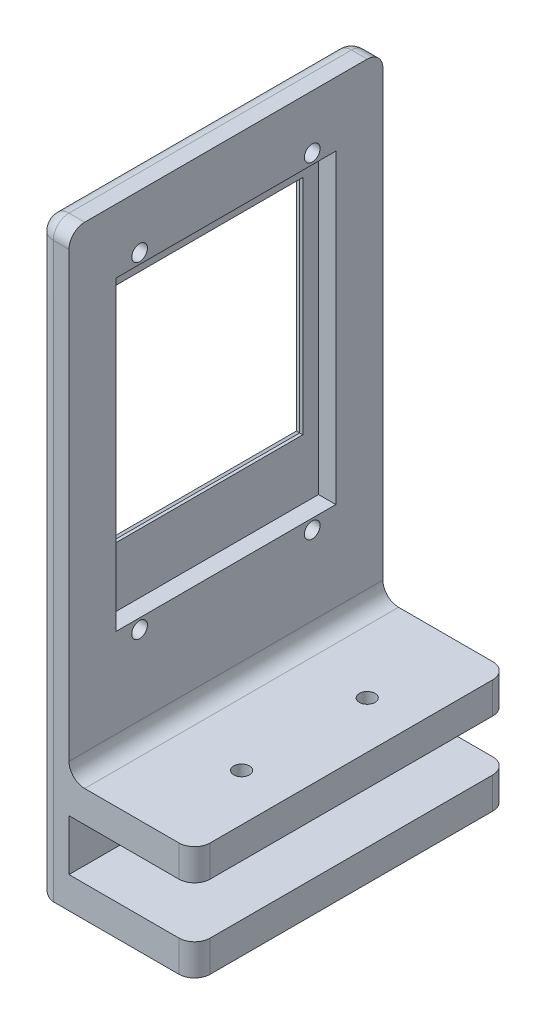
SolidWorks part; units mm, degrees
ref_plane "Front Plane" through (0, 0, 0) normal (0, 0, 1) x (1, 0, 0)
ref_plane "Top Plane" through (0, 0, 0) normal (0, 1, 0) x (1, 0, 0)
ref_plane "Right Plane" through (0, 0, 0) normal (1, 0, 0) x (0, 0, -1)
sketch "Sketch12" plane through (0, 0, 0) normal (0, 0, 1) x (1, 0, 0)
  line L0 (0, -38.4175) -> (20.32, -38.4175)
  line L1 (-5.08, 38.4175) -> (0, 38.4175)
  line L2 (-5.08, 38.4175) -> (-5.08, -56.8325)
  line L4 (0, 38.4175) -> (0, -38.4175)
  line L5 (20.32, -38.4175) -> (20.32, -43.4975)
  line L6 (20.32, -43.4975) -> (0, -43.4975)
  line L7 (0, -43.4975) -> (0, -51.7525)
  line L8 (20.32, -56.8325) -> (20.32, -51.7525)
  line L9 (20.32, -51.7525) -> (0, -51.7525)
  line L11 (20.32, -56.8325) -> (-5.08, -56.8325)
  dimension "D1" = 8.255
  dimension "D2" = 5.08
  dimension "D3" = 5.08
  dimension "D4" = 25.4
  dimension "D5" = 95.25
extrude "Boss-Extrude7" add sketch "Sketch12" along normal mid plane 50.8
sketch "Sketch14" plane through (0, 0, 0) normal (1, 0, 0) x (0, 0, -1)
  line L0 (-25.4, -43.4975) -> (25.4, -43.4975) construction
  line L1 (-15.24, 24.2443) -> (15.24, 24.2443)
  line L2 (-15.24, 24.2443) -> (-15.24, -11.8237)
  line L3 (-15.24, -11.8237) -> (15.24, -11.8237)
  line L4 (15.24, 24.2443) -> (15.24, -11.8237)
  line L5 (-15.24, 24.2443) -> (15.24, -11.8237) construction
  line L6 (-15.24, -11.8237) -> (15.24, 24.2443) construction
  point P0 (0, 6.2103)
  dimension "D1" = 36.068
  dimension "D2" = 30.48
  dimension "D3" = 49.7078
extrude "Cut-Extrude3" cut sketch "Sketch14" against normal through all
sketch "Sketch15" plane through (0, 0, 0) normal (1, 0, 0) x (0, 0, -1)
  line L0 (15.24, 24.2443) -> (-15.24, 24.2443) construction
  line L1 (-17.78, 28.0543) -> (17.78, 28.0543)
  line L2 (-17.78, 28.0543) -> (-17.78, -21.4757)
  line L3 (-17.78, -21.4757) -> (17.78, -21.4757)
  line L4 (17.78, 28.0543) -> (17.78, -21.4757)
  line L5 (-17.78, 28.0543) -> (17.78, -21.4757) construction
  line L6 (-17.78, -21.4757) -> (17.78, 28.0543) construction
  point P0 (0, 3.2893)
  dimension "D1" = 35.56
  dimension "D2" = 49.53
  dimension "D3" = 3.81
extrude "Cut-Extrude4" cut sketch "Sketch15" against normal blind 2.794
chamfer "Chamfer1" distance 1.778 angle 35 4 edges at (-5.08, -11.8237, 0) (-5.08, 6.2103, 15.24) (-5.08, 24.2443, 0) (-5.08, 6.2103, -15.24)
sketch "Sketch16" plane through (0, 0, 0) normal (1, 0, 0) x (0, 0, -1)
  line L0 (-25.4, 6.2103) -> (25.4, 6.2103) construction
  line L1 (25.4, -38.4175) -> (25.4, 38.4175) construction
  line L2 (-25.4, -38.4175) -> (-25.4, 38.4175) construction
  line L3 (-15.24, 24.2443) -> (15.24, 24.2443) construction
  circle A0 centre (-13.97, 29.7053) radius 1.27
  circle A1 centre (13.97, 29.7053) radius 1.27
  circle A2 centre (-13.97, -23.1267) radius 1.27
  circle A3 centre (13.97, -23.1267) radius 1.27
  dimension "D1" = 2.54
  dimension "D2" = 27.94
  dimension "D3" = 52.832
  dimension "D4" = 13.97
  dimension "D5" = 18.034
  dimension "D6" = 23.495
extrude "Cut-Extrude5" cut sketch "Sketch16" against normal through all
sketch "Sketch21" [suppressed] plane through (-2.794, 0, 0) normal (1, 0, 0) x (0, 0, -1)
  line L0 (15.24, 24.2443) -> (15.24, -11.8237) construction
  line L1 (15.24, 6.2103) -> (-15.24, 6.2103) construction
  line L2 (-15.24, -11.8237) -> (-15.24, 24.2443) construction
  point P0 (15.24, 6.2103)
fillet "Fillet4" radius 2.54 2 edges at (-2.54, 38.4175, -25.4) (-2.54, 38.4175, 25.4)
fillet "Fillet5" radius 2.54 4 edges at (20.32, -54.2925, 25.4) (20.32, -40.9575, 25.4) (20.32, -54.2925, -25.4) (20.32, -40.9575, -25.4)
sketch "Sketch23" plane through (0, -51.7525, 0) normal (0, 1, 0) x (1, 0, 0)
  line L0 (8.89, 25.4) -> (8.89, -25.4) construction
  line L1 (17.78, 25.4) -> (0, 25.4) construction
  line L2 (17.78, -25.4) -> (0, -25.4) construction
  line L3 (0, -25.4) -> (0, 25.4) construction
  circle A0 centre (8.89, 15.24) radius 1.778
  circle A1 centre (8.89, -15.24) radius 1.778
  point P10 (0, 0)
  point P13 (0, 0)
  dimension "D1" = 3.556
  dimension "D2" = 15.24
  dimension "D3" = 15.24
extrude "Cut-Extrude6" cut sketch "Sketch23" against normal through all
fillet "Fillet6" radius 2.54 6 edges at (-5.08, -10.4775, 25.4) (-5.08, 37.6736, 24.6561) (-5.08, 38.4175, 0) (-5.08, 37.6736, -24.6561) (-5.08, -10.4775, -25.4) (-5.08, -56.8325, 0)
sketch "Sketch24" plane through (0, -38.4175, 0) normal (0, 1, 0) x (1, 0, 0)
  circle A0 centre (12.7, 10.16) radius 1.27
  circle A1 centre (12.7, -10.16) radius 1.27
  dimension "D1" = 2.54
  dimension "D2" = 20.32
  dimension "D3" = 10.16
  dimension "D4" = 12.7
extrude "Cut-Extrude7" cut sketch "Sketch24" against normal up to next
fillet "Fillet7" radius 2.54 1 edges at (0, -38.4175, 0)
